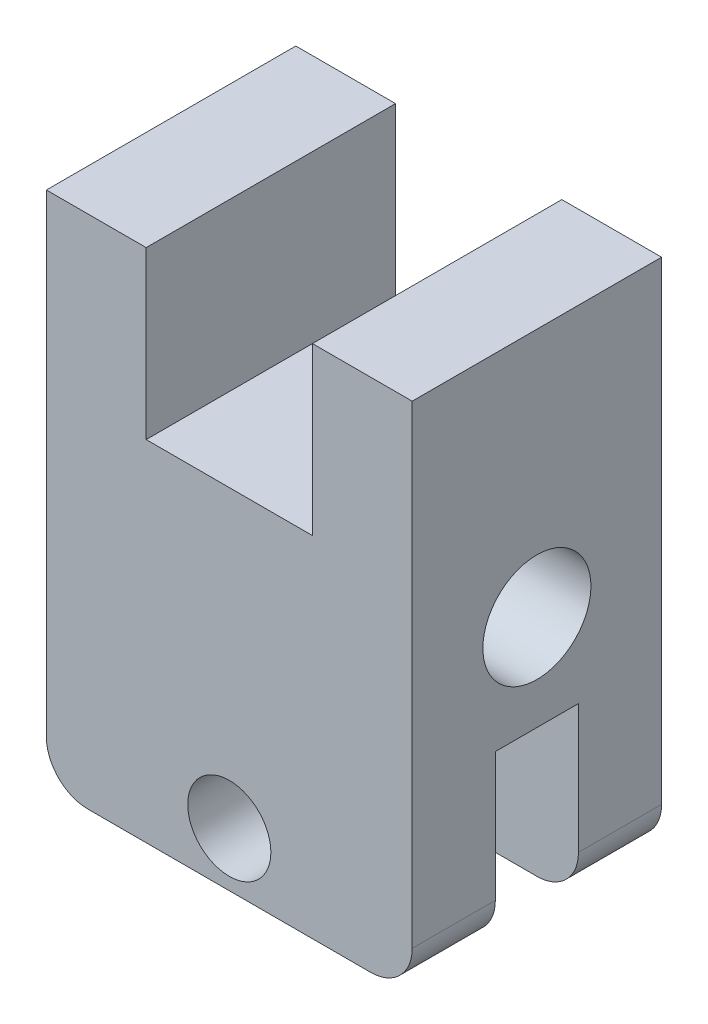
SolidWorks part; units mm, degrees
ref_plane "Alzado" through (0, 0, 0) normal (0, 0, 1) x (1, 0, 0)
ref_plane "Planta" through (0, 0, 0) normal (0, 1, 0) x (1, 0, 0)
ref_plane "Vista lateral" through (0, 0, 0) normal (1, 0, 0) x (0, 0, -1)
sketch "Croquis1" plane through (0, 0, 0) normal (0, 0, 1) x (1, 0, 0)
  line L0 (0, 25) -> (0, 0) construction
  line L1 (-22, 35) -> (22, 35)
  line L2 (-22, 35) -> (-22, -35)
  line L3 (-22, -35) -> (22, -35)
  line L4 (22, 35) -> (22, -35)
  line L5 (-22, 35) -> (22, -35) construction
  line L6 (-22, -35) -> (22, 35) construction
  line L7 (0, 0) -> (0, -20.5) construction
  line L8 (-10, 15) -> (10, 15)
  line L9 (-10, 15) -> (-10, 35)
  line L10 (-10, 35) -> (10, 35)
  line L11 (10, 15) -> (10, 35)
  line L12 (-10, 15) -> (10, 35) construction
  line L13 (-10, 35) -> (10, 15) construction
  circle A0 centre (0, -20.5) radius 5
  point P0 (0, 0)
  point P8 (0, 25)
  dimension "D4" = 10
  dimension "D1" = 20
  dimension "D2" = 20
  dimension "D3" = 50
  dimension "D5" = 20.5
  dimension "D6" = 44
extrude "Base" add sketch "Croquis1" along normal blind 30 contours L11 L8 L9 L1 L2 L3 L4 A0
sketch "Croquis4" plane through (22, 0, 0) normal (1, 0, 0) x (0, 0, -1)
  line L0 (-15, 35) -> (-15, 15) construction
  line L1 (-30, 35) -> (0, 35) construction
  line L2 (-15, 15) -> (-15, 5) construction
  circle A0 centre (-15, 5) radius 7.5
  dimension "D2" = 15
  dimension "D1" = 20
  dimension "D3" = 10
extrude "Cortar-Extruir3" cut sketch "Croquis4" against normal through all
sketch "Croquis7" plane through (22, 0, 0) normal (1, 0, 0) x (0, 0, -1)
  line L0 (-15, -35) -> (-15, -6.5) construction
  line L1 (-30, -35) -> (0, -35) construction
  line L2 (-10, -35) -> (-10, -6.5)
  line L3 (-20, -35) -> (-20, -6.5)
  line L4 (-10, -6.5) -> (-20, -6.5)
  line L5 (-10, -35) -> (-20, -35)
  dimension "D1" = 5
  dimension "D3" = 28.5
  dimension "D2" = 5
extrude "Cortar-Extruir6" cut sketch "Croquis7" against normal through all
sketch "Croquis8" plane through (0, 0, 30) normal (0, 0, 1) x (1, 0, 0)
  line L0 (22, 35) -> (22, -35) construction
  line L1 (-22, -35) -> (22, -35)
  line L2 (-22, -35) -> (-22, -27)
  line L3 (-22, -27) -> (22, -27)
  line L4 (22, -35) -> (22, -27)
  dimension "D1" = 8
extrude "Cortar-Extruir7" cut sketch "Croquis8" against normal through all
fillet "Redondeo3" radius 5 4 edges at (-22, -27, 5) (-22, -27, 25) (22, -27, 5) (22, -27, 25)
sketch "Croquis10" plane through (22, 0, 0) normal (1, 0, 0) x (0, 0, -1)
  circle A0 centre (-15, 5) radius 7.5
  circle A1 centre (-15, 5) radius 6.5
  dimension "D1" = 15
  dimension "D2" = 1
extrude "Saliente-Extruir2" add sketch "Croquis10" against normal blind 10
